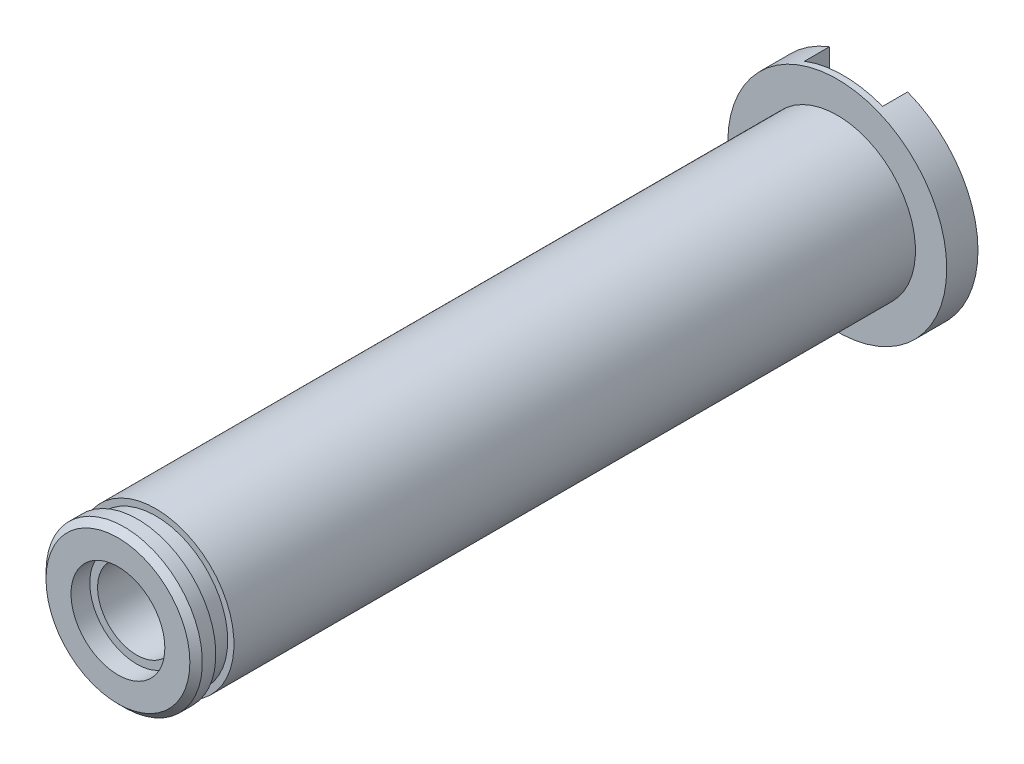
SolidWorks part; units mm, degrees
ref_plane "Front Plane" through (0, 0, 0) normal (0, 0, 1) x (1, 0, 0)
ref_plane "Top Plane" through (0, 0, 0) normal (0, 1, 0) x (1, 0, 0)
ref_plane "Right Plane" through (0, 0, 0) normal (1, 0, 0) x (0, 0, -1)
sketch "Sketch2" plane through (0, 0, 0) normal (0, 0, 1) x (1, 0, 0)
  circle A0 centre (0, 0) radius 4.445
extrude "Boss-Extrude1" add sketch "Sketch2" along normal blind 1.27
sketch "Sketch3" plane through (0, 0, 1.27) normal (0, 0, 1) x (1, 0, 0)
  circle A0 centre (0, 0) radius 3.175
extrude "Boss-Extrude2" add sketch "Sketch3" along normal blind 29.21
sketch "Sketch4" plane through (0, 0, 30.48) normal (0, 0, 1) x (1, 0, 0)
  circle A0 centre (0, 0) radius 1.5875
extrude "Cut-Extrude1" cut sketch "Sketch4" against normal blind 37.592
sketch "Sketch5" plane through (0, 0, 30.48) normal (0, 0, 1) x (1, 0, 0)
  circle A0 centre (0, 0) radius 1.905
extrude "Cut-Extrude2" cut sketch "Sketch5" against normal blind 0.762
sketch "Sketch6" plane through (0, 0, 0) normal (0, 0, -1) x (-1, 0, 0)
  line L5 (-1.5875, 5.8734) -> (1.5875, 5.8734)
  line L6 (-1.5875, 5.8734) -> (-1.5875, 0)
  line L7 (-1.5875, 0) -> (1.5875, 0)
  line L8 (1.5875, 5.8734) -> (1.5875, 0)
  dimension "D1" = 0
  dimension "D2" = 3.175
  dimension "D3" = 1.5875
extrude "Cut-Extrude3" cut sketch "Sketch6" against normal blind 1.016
sketch3d "3DSketch1" plane through (0, 0, 0) normal (0, 0, 1) x (1, 0, 0)
  dimension "D1" = 0.8001
sketch "Sketch7" plane through (0, 0, 29.6799) normal (0, 0, 1) x (1, 0, 0)
  circle A0 centre (0, 0) radius 3.175
  circle A1 centre (0, 0) radius 2.921
extrude "Cut-Extrude5" cut sketch "Sketch7" against normal blind 0.7366
chamfer "Chamfer1" distance 0.254 angle 45 1 edges at (3.175, 0, 30.48)
